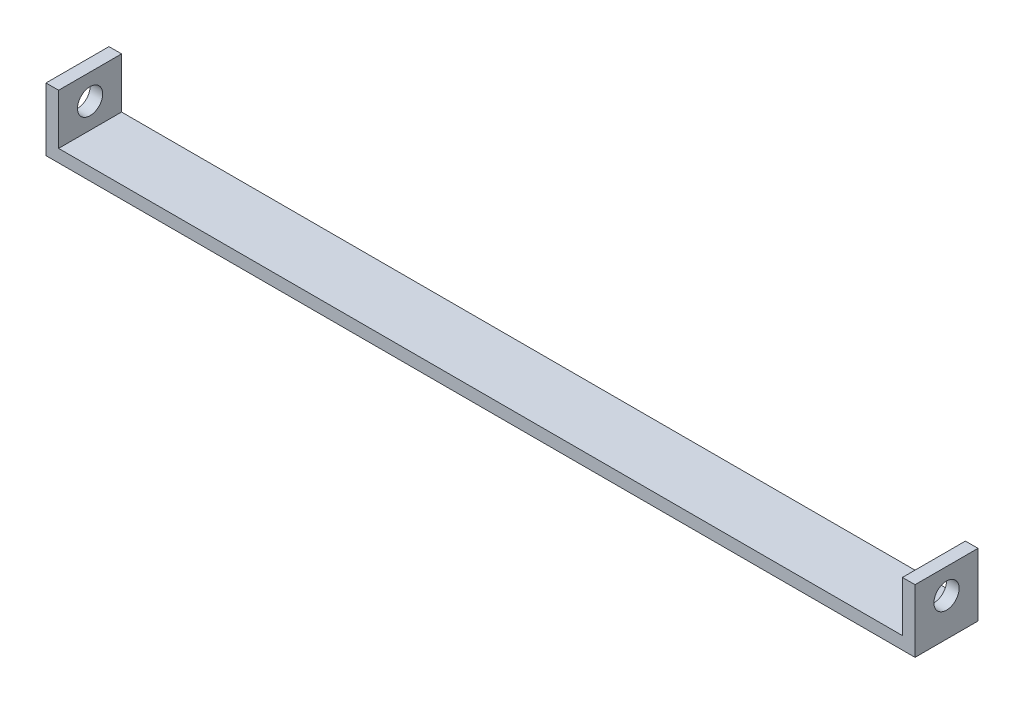
SolidWorks part; units mm, degrees
ref_plane "Front Plane" through (0, 0, 0) normal (0, 0, 1) x (1, 0, 0)
ref_plane "Top Plane" through (0, 0, 0) normal (0, 1, 0) x (1, 0, 0)
ref_plane "Right Plane" through (0, 0, 0) normal (1, 0, 0) x (0, 0, -1)
sketch "Sketch1" plane through (0, 0, 0) normal (0, 0, 1) x (1, 0, 0)
  line L0 (0, 0) -> (138, 0)
  line L1 (138, 0) -> (138, 10)
  line L2 (138, 10) -> (136, 10)
  line L3 (136, 10) -> (136, 2)
  line L4 (136, 2) -> (2, 2)
  line L5 (2, 2) -> (2, 10)
  line L6 (2, 10) -> (0, 10)
  line L7 (0, 10) -> (0, 0)
  dimension "D1" = 138
  dimension "D2" = 10
  dimension "D3" = 2
  dimension "D4" = 2
  dimension "D5" = 2
extrude "Boss-Extrude1" add sketch "Sketch1" along normal blind 10
sketch "Sketch2" plane through (0, 2, 0) normal (0, 1, 0) x (1, 0, 0)
  line L0 (2, 0) -> (136, -10) construction
  circle A0 centre (69, -5) radius 1.5
  point P7 (69, -5)
  dimension "D1" = 3
extrude "Cut-Extrude1" [suppressed] cut sketch "Sketch2" against normal up to surface (3 mm away)
sketch "Sketch3" plane through (0, 0, 0) normal (-1, 0, 0) x (0, 0, 1)
  line L0 (10, 10) -> (0, 10) construction
  line L1 (0, 10) -> (0, 0) construction
  circle A0 centre (5, 6) radius 2
  dimension "D1" = 4
  dimension "D2" = 4
  dimension "D3" = 5
extrude "Cut-Extrude2" cut sketch "Sketch3" against normal up to surface (136 mm away)
ref_plane "Plane1" through (69, 0, 0) normal (-1, 0, 0) x (0, 0, 1)
mirror "Mirror1" about plane through (69, 0, 0) normal (-1, 0, 0) of "Cut-Extrude2"
equation "\"D4@Sketch1\"=\"D3@Sketch1\""
equation "\"D5@Sketch1\"=\"D3@Sketch1\""
